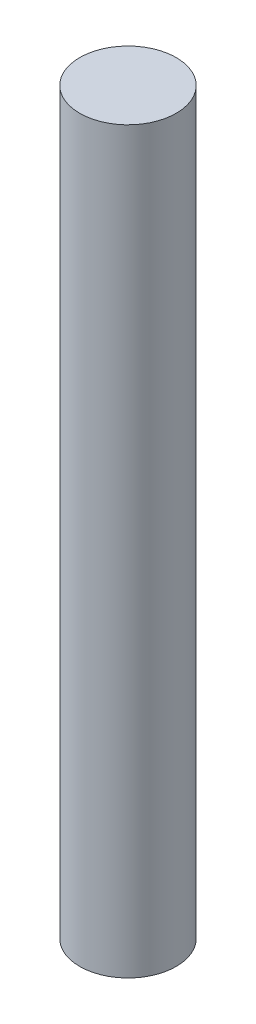
SolidWorks part; units mm, degrees
ref_plane "前视基准面" through (0, 0, 0) normal (0, 0, 1) x (1, 0, 0)
ref_plane "上视基准面" through (0, 0, 0) normal (0, 1, 0) x (1, 0, 0)
ref_plane "右视基准面" through (0, 0, 0) normal (1, 0, 0) x (0, 0, -1)
sketch "草图1" plane through (0, 0, 0) normal (0, 1, 0) x (1, 0, 0)
  circle A0 centre (0, 0) radius 4.9
  dimension "D1" = 9.8
extrude "凸台-拉伸1" add sketch "草图1" along normal blind 75
